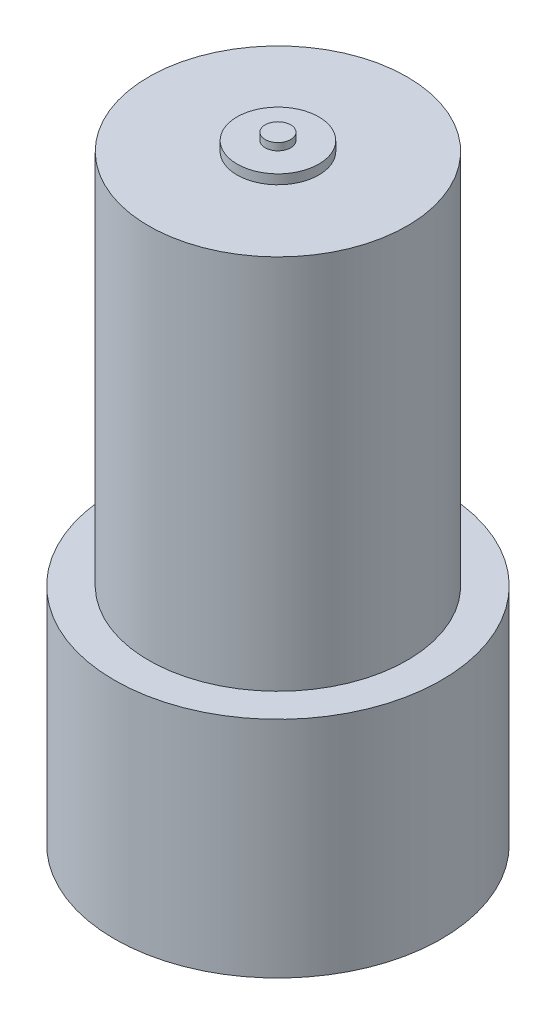
SolidWorks part; units mm, degrees
ref_plane "Front Plane" through (0, 0, 0) normal (0, 0, 1) x (1, 0, 0)
ref_plane "Top Plane" through (0, 0, 0) normal (0, 1, 0) x (1, 0, 0)
ref_plane "Right Plane" through (0, 0, 0) normal (1, 0, 0) x (0, 0, -1)
sketch "Sketch1" plane through (0, 0, 0) normal (0, 1, 0) x (1, 0, 0)
  line L0 (-55, 0) -> (55, 0) construction
  line L1 (0, -55) -> (0, 55) construction
  circle A0 centre (0, 0) radius 25.4
extrude "Boss-Extrude1" add sketch "Sketch1" along normal blind 34.798
sketch "Sketch2" plane through (0, 34.798, 0) normal (0, 1, 0) x (-1, 0, 0)
  circle A0 centre (0, 0) radius 20.066
extrude "Boss-Extrude2" add sketch "Sketch2" along normal blind 58.42
sketch "Sketch3" plane through (0, 0, 0) normal (0, -1, 0) x (1, 0, 0)
  circle A0 centre (0, 0) radius 14.224
extrude "Boss-Extrude3" add sketch "Sketch3" along normal blind 1.524
sketch "Sketch4" plane through (0, 93.218, 0) normal (0, 1, 0) x (-1, 0, 0)
  circle A0 centre (0, 0) radius 6.35
extrude "Boss-Extrude4" add sketch "Sketch4" along normal blind 1.4732
sketch "Sketch5" plane through (0, 94.6912, 0) normal (0, 1, 0) x (1, 0, 0)
  circle A0 centre (0, 0) radius 1.9812
extrude "Boss-Extrude5" add sketch "Sketch5" along normal blind 1.1176
sketch "Sketch6" plane through (0, 0, 0) normal (0, -1, 0) x (1, 0, 0)
  circle A0 centre (-4.1783, 0) radius 2.9464
  circle A1 centre (0, 0) radius 4.1783 construction
  dimension "D1" = 8.3566
  dimension "D2" = 5.8928
extrude "Boss-Extrude6" add sketch "Sketch6" along normal blind 17.526
sketch "Sketch8" plane through (0, 0, 0) normal (0, -1, 0) x (1, 0, 0)
  point P0 (0, 19.05)
  point P1 (0, -19.05)
  dimension "D1" = 19.05
  dimension "D2" = 19.05
hole_wizard "#10-32 Tapped Hole1" positions "Sketch10" profile "Sketch9" tap size "#10-32" standard "Ansi Inch"
sketch "Sketch10" plane through (0, 0, 0) normal (0, -1, 0) x (1, 0, 0)
  point P1 (0, 19.05)
  point P4 (0, -19.05)
sketch "Sketch9" plane through (0, 0, 19.05) normal (1, 0, 0) x (0, 0, -1)
  line L0 (0, 0) -> (0, 7.5633)
  line L1 (0, 7.5633) -> (2.0193, 6.35)
  line L2 (2.0193, 6.35) -> (2.0193, 0)
  line L5 (2.0193, 0) -> (0, 0)
  line L10 (0, 7.5633) -> (-2.0193, 6.35) construction
  line L11 (0, -6.35) -> (0, 107.95) construction
  dimension "Tap Drill Dia." = 4.0386
  dimension "Tap Drill Depth" = 6.35
  dimension "Drill Angle" = 118
cosmetic thread "Hole Thread1" parameters "D1"=6.35, "D2"=4.826
cosmetic thread "Hole Thread2" parameters "D1"=6.35, "D2"=4.826
